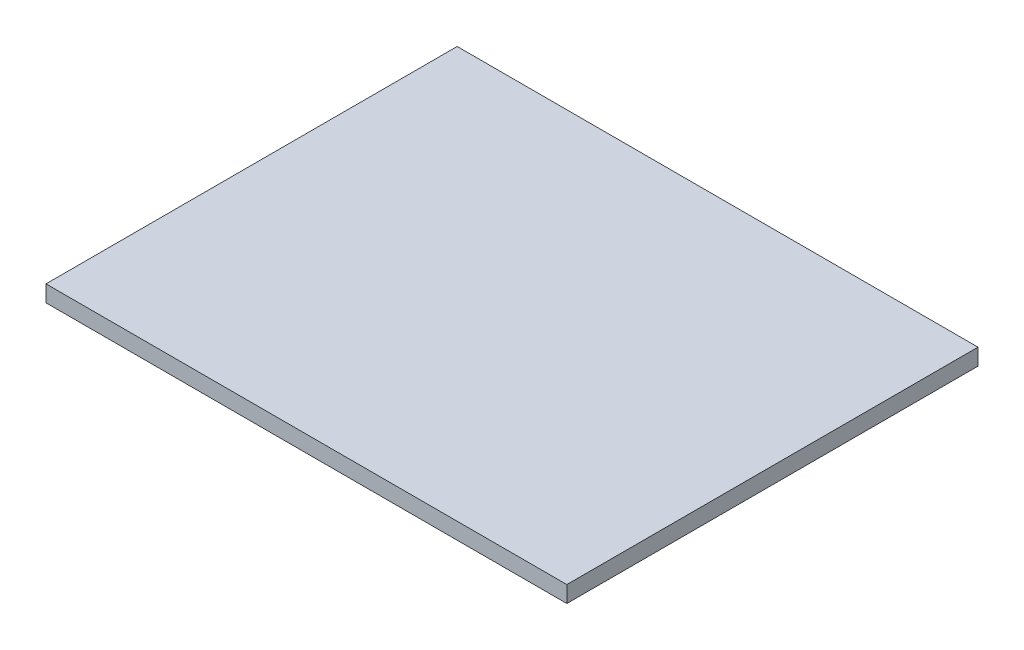
SolidWorks part; units mm, degrees
ref_plane "Front Plane" through (0, 0, 0) normal (0, 0, 1) x (1, 0, 0)
ref_plane "Top Plane" through (0, 0, 0) normal (0, 1, 0) x (1, 0, 0)
ref_plane "Right Plane" through (0, 0, 0) normal (1, 0, 0) x (0, 0, -1)
sketch "Sketch1" plane through (0, 0, 0) normal (0, 1, 0) x (1, 0, 0)
  line L1 (47.5, -37.5) -> (-47.5, -37.5)
  line L2 (47.5, -37.5) -> (47.5, 37.5)
  line L3 (47.5, 37.5) -> (-47.5, 37.5)
  line L4 (-47.5, -37.5) -> (-47.5, 37.5)
  line L5 (47.5, -37.5) -> (-47.5, 37.5) construction
  line L6 (47.5, 37.5) -> (-47.5, -37.5) construction
  point P0 (0, 0)
  dimension "D1" = 95
  dimension "D2" = 75
extrude "Boss-Extrude1" add sketch "Sketch1" along normal blind 3
